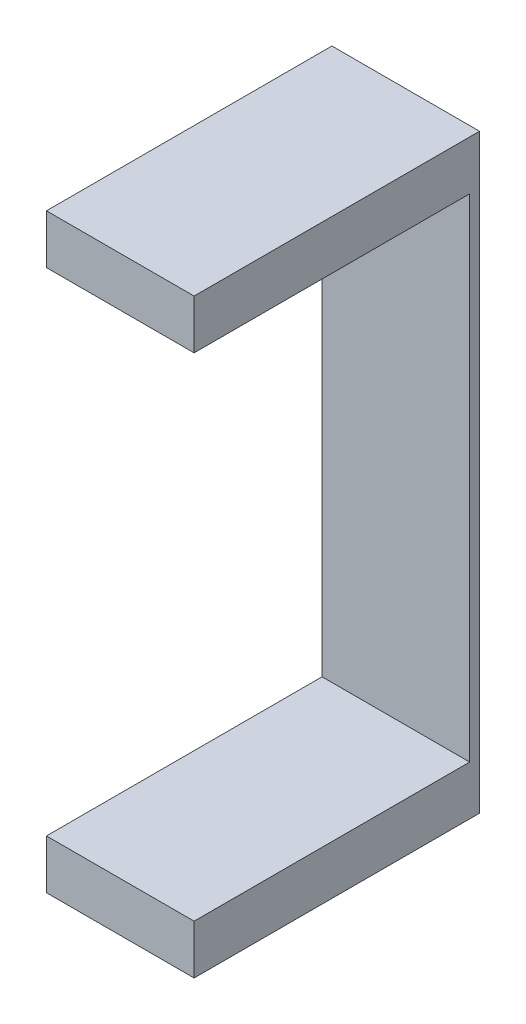
SolidWorks part; units mm, degrees
ref_plane "Front Plane" through (0, 0, 0) normal (1, 0, 0) x (0, 1, 0)
ref_plane "Top Plane" through (0, 0, 0) normal (0, 0, 1) x (0, 1, 0)
ref_plane "Right Plane" through (0, 0, 0) normal (0, 1, 0) x (-1, 0, 0)
sketch "Sketch2" plane through (0, 0, 0) normal (0, 0, 1) x (0, 1, 0)
  line L1 (-60, 15) -> (60, 15)
  line L2 (-60, 15) -> (-60, -15)
  line L3 (-60, -15) -> (60, -15)
  line L4 (60, 15) -> (60, -15)
  line L5 (-60, 15) -> (60, -15) construction
  line L6 (-60, -15) -> (60, 15) construction
  point P0 (0, 0)
  dimension "D1" = 120
  dimension "D2" = 30
extrude "Boss-Extrude1" add sketch "Sketch2" along normal blind 2
sketch "Sketch3" plane through (0, 0, 2) normal (0, 0, 1) x (1, 0, 0)
  line L0 (15, -60) -> (15, 60) construction
  line L1 (-15, 60) -> (15, 60)
  line L2 (-15, 60) -> (-15, 50)
  line L3 (-15, 50) -> (15, 50)
  line L4 (15, 60) -> (15, 50)
  line L6 (-15, -60) -> (15, -60)
  line L7 (-15, -60) -> (-15, -50)
  line L8 (-15, -50) -> (15, -50)
  line L9 (15, -60) -> (15, -50)
  dimension "D1" = 10
  dimension "D2" = 10
extrude "Boss-Extrude2" add sketch "Sketch3" along normal blind 56
